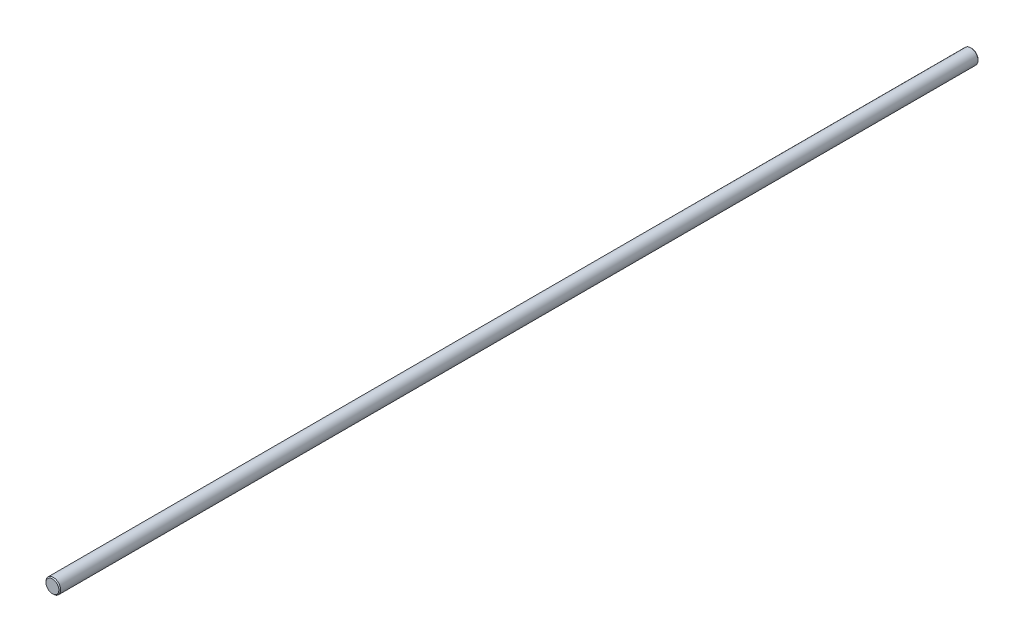
SolidWorks part; units mm, degrees
material "普通碳钢"
ref_plane "前视基准面" through (0, 0, 0) normal (0, 0, 1) x (1, 0, 0)
ref_plane "上视基准面" through (0, 0, 0) normal (0, 1, 0) x (1, 0, 0)
ref_plane "右视基准面" through (0, 0, 0) normal (1, 0, 0) x (0, 0, -1)
other "Configuration Table"
sketch "草图1" plane through (0, 0, 0) normal (0, 0, 1) x (1, 0, 0)
  circle A0 centre (0, 0) radius 4
  dimension "D1" = 8
extrude "凸台-拉伸1" add sketch "草图1" along normal mid plane 500
chamfer "倒角1" distance 0.5 angle 45 2 edges at (4, 0, 250) (4, 0, -250)
